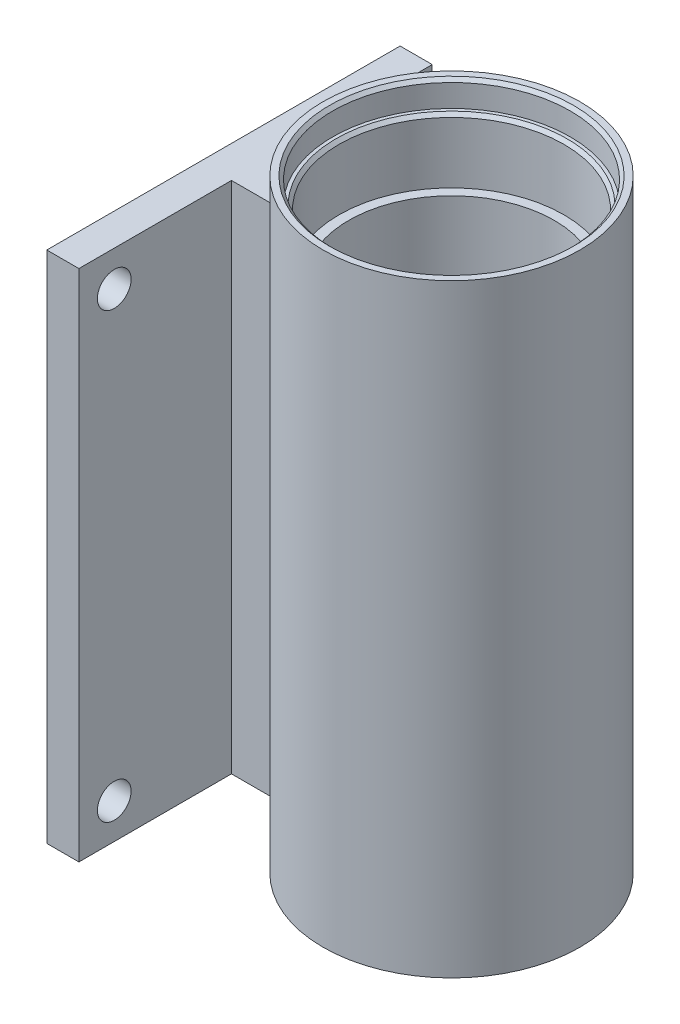
SolidWorks part; units mm, degrees
material "Carburized and nitrided special steel"
ref_plane "Piano frontale" through (0, 0, 0) normal (0, 0, 1) x (1, 0, 0)
ref_plane "Piano superiore" through (0, 0, 0) normal (0, 1, 0) x (1, 0, 0)
ref_plane "Piano destro" through (0, 0, 0) normal (1, 0, 0) x (0, 0, -1)
sketch "Schizzo1" plane through (0, 0, 0) normal (0, 1, 0) x (1, 0, 0)
  line L0 (0, 0) -> (-140.3856, 0) construction
  line L1 (-39.2906, 7.5) -> (-61, 7.5)
  line L2 (-71, 55) -> (-71, -55)
  line L3 (-61, 55) -> (-61, 7.5)
  line L4 (-71, 55) -> (-61, 55)
  line L5 (-71, -55) -> (-61, -55)
  line L6 (-61, -55) -> (-61, -7.5)
  line L7 (-39.2906, -7.5) -> (-61, -7.5)
  arc A0 (-39.2906, -7.5) -> (-39.2906, 7.5) centre (0, 0) ccw
  circle A1 centre (0, 0) radius 32
  point P12 (-71, 0)
  dimension "D1" = 80
  dimension "D2" = 64
  dimension "D3" = 7.5
  dimension "D4" = 71
  dimension "D5" = 10
  dimension "D6" = 55
extrude "Estrusione1" add sketch "Schizzo1" along normal blind 160
sketch "Schizzo2" plane through (0, 160, 0) normal (0, 1, 0) x (1, 0, 0)
  circle A0 centre (0, 0) radius 40
  circle A1 centre (0, 0) radius 35
extrude "Estrusione2" add sketch "Schizzo2" along normal blind 20
sketch "Schizzo4" plane through (-71, 0, 0) normal (-1, 0, 0) x (0, 0, 1)
  line L0 (0, 160) -> (0, -13.7591) construction
  line L1 (-55, 160) -> (55, 160) construction
  line L2 (-55, 80) -> (101.4749, 80) construction
  line L3 (-55, 160) -> (-55, 0) construction
  circle A0 centre (-44, 149) radius 5.25
  circle A1 centre (44, 149) radius 5.25
  circle A2 centre (44, 11) radius 5.25
  circle A3 centre (-44, 11) radius 5.25
  dimension "D1" = 44
  dimension "D2" = 69
extrude "Estrusione4" cut sketch "Schizzo4" against normal blind 20
sketch "Schizzo5" plane through (-71, 0, 0) normal (-1, 0, 0) x (0, 0, 1)
  line L0 (0, 0) -> (0, 164.8742) construction
  line L1 (-55, 80) -> (66.6368, 80) construction
  line L2 (-55, 160) -> (-55, 0) construction
  circle A0 centre (0, 149) radius 4
  circle A1 centre (0, 11) radius 4
  dimension "D1" = 69
  dimension "D2" = 8
extrude "Estrusione5" cut sketch "Schizzo5" against normal blind 12
sketch "Schizzo6" plane through (0, 180, 0) normal (0, 1, 0) x (1, 0, 0)
  circle A0 centre (0, 0) radius 37
  circle A1 centre (0, 0) radius 40
extrude "Estrusione6" add sketch "Schizzo6" along normal blind 8
sketch "Schizzo7" plane through (0, 0, 0) normal (0, -1, 0) x (1, 0, 0)
  circle A0 centre (0, 0) radius 35
  dimension "D1" = 70
extrude "Estrusione7" cut sketch "Schizzo7" against normal blind 20
chamfer "Smusso1" distance 1 angle 45 3 edges at (0, 180, 35) (0, 188, 37) (0, 0, -35)
